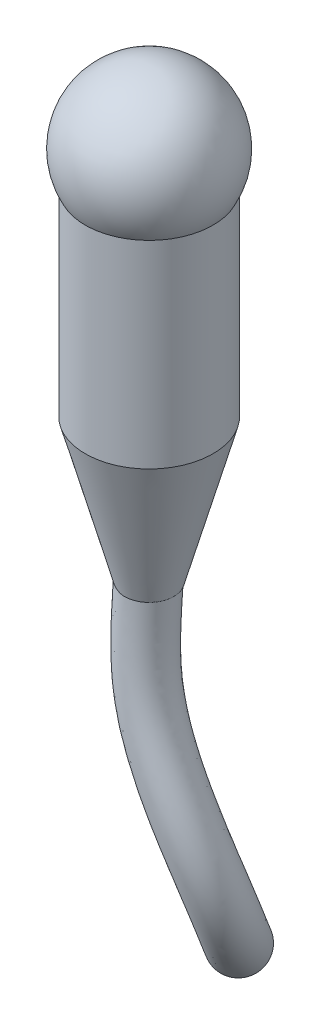
SolidWorks part; units mm, degrees
ref_plane "Front Plane" through (0, 0, 0) normal (0, 0, 1) x (1, 0, 0)
ref_plane "Top Plane" through (0, 0, 0) normal (0, 1, 0) x (1, 0, 0)
ref_plane "Right Plane" through (0, 0, 0) normal (1, 0, 0) x (0, 0, -1)
sketch "Sketch1" plane through (0, 0, 0) normal (0, 0, 1) x (1, 0, 0)
  line L0 (0, 0) -> (0, 72.4784) construction
  line L1 (-7.75, 54.2126) -> (-7.75, 30.2126)
  line L2 (-7.75, 30.2126) -> (-3, 12.8507)
  line L3 (0, 67.1813) -> (0, 12.8507)
  line L4 (-3, 12.8507) -> (0, 12.8507)
  arc A0 (-7.75, 54.2126) -> (0, 67.1813) centre (0, 58.3813) cw
  dimension "D2" = 8.8
  dimension "D1" = 7.75
  dimension "D3" = 24
  dimension "D4" = 3
  dimension "D5" = 18
revolve "Revolve1" add sketch "Sketch1" angle 360 about L0
sketch "Sketch2" plane through (0, 0, 0) normal (0, 0, 1) x (1, 0, 0)
  spline S0 degree 3 poles (0, 16.2683) (-0.1464, 11.5568) (-1.6086, -4.8726) (12.4029, -17.475) (3.1453, -27.7902) knots 0 0 0 0 0.30084 1 1 1 1
sketch "Sketch3" plane through (0, 0, 0) normal (1, 0, 0) x (0, 0, -1)
  spline S0 degree 3 poles (0, 16.2683) (0.3589, 2.2168) (-3.8384, -13.5019) (6.0872, -25.7366) knots 0 0 0 0 1 1 1 1
curve "Curve1"
sweep "Sweep1" add path "Curve1" circular profile diameter 6 parameters "D3"=6
